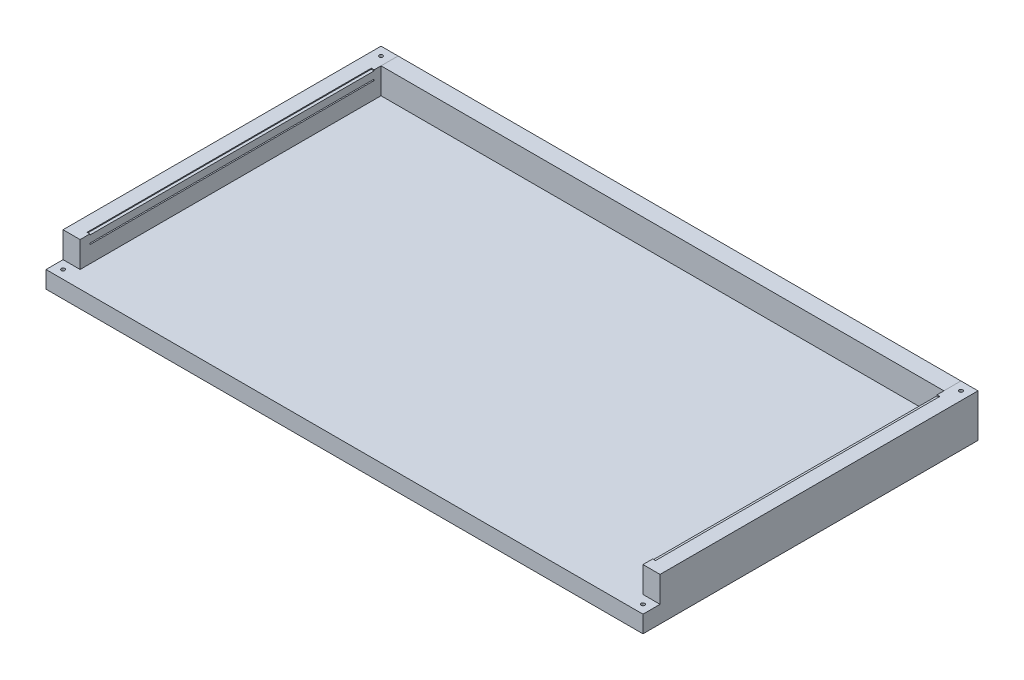
SolidWorks part; units mm, degrees
ref_plane "Front Plane" through (0, 0, 0) normal (0, 0, 1) x (1, 0, 0)
ref_plane "Top Plane" through (0, 0, 0) normal (0, 1, 0) x (1, 0, 0)
ref_plane "Right Plane" through (0, 0, 0) normal (1, 0, 0) x (0, 0, -1)
sketch "Sketch3" plane through (0, 0, 0) normal (0, 0, 1) x (1, 0, 0)
  line L1 (-990, 60) -> (990, 60)
  line L3 (-1050, 0) -> (1050, 0)
  line L5 (-1050, 151.2) -> (-990, 151.2)
  line L6 (-990, 151.2) -> (-990, 60)
  line L7 (0, 0) -> (0, 60) construction
  line L8 (990, 151.2) -> (990, 60)
  line L9 (1050, 151.2) -> (990, 151.2)
  line L11 (1050, 151.2) -> (1050, 0)
  line L12 (-1050, 151.2) -> (-1050, 0)
  dimension "D3" = 60
  dimension "D4" = 91.2
  dimension "D5" = 60
  dimension "D1" = 1980
extrude "Boss-Extrude1" add sketch "Sketch3" along normal mid plane 1118.5
sketch "Sketch4" plane through (0, 0, 0) normal (0, 1, 0) x (1, 0, 0)
  line L0 (-990, 559.25) -> (-990, 499.25)
  line L1 (-990, -559.25) -> (-990, 559.25) construction
  line L2 (-990, 499.25) -> (990, 499.25)
  line L3 (990, -559.25) -> (990, 559.25) construction
  line L4 (990, 499.25) -> (990, 559.25)
  line L5 (990, 559.25) -> (-990, 559.25)
  dimension "D1" = 60
extrude "Boss-Extrude2" add sketch "Sketch4" along normal up to surface (151.2 mm away) from surface at 0 separate body up to face at (-1020, 151.2, 0) starting at face at (0, 0, 0)
sketch "Sketch6" plane through (0, 0, 0) normal (0, 0, 1) x (1, 0, 0)
  line L0 (1000, 151.2) -> (-1000, 151.2)
  line L1 (-990, 151.2) -> (-990, 0) construction
  line L2 (-1000, 151.2) -> (-1000, 147.9)
  line L3 (-1000, 147.9) -> (1000, 147.9)
  line L4 (1000, 147.9) -> (1000, 151.2)
  line L7 (-1000, 122.9) -> (1000, 122.9)
  line L8 (1000, 122.9) -> (1000, 118.5)
  line L9 (1000, 118.5) -> (-1000, 118.5)
  line L10 (-1000, 118.5) -> (-1000, 122.9)
  line L11 (990, 151.2) -> (990, 60) construction
  line L12 (-1050, 0) -> (1050, 0) construction
  dimension "D2" = 10
  dimension "D5" = 4.4
  dimension "D1" = 3.3
  dimension "D6" = 118.5
  dimension "D3" = 10
  dimension "D4" = 25
extrude "Cut-Extrude2" cut sketch "Sketch6" against normal mid plane 1000 from offset 25
sketch "Sketch7" plane through (0, 0, 0) normal (0, 1, 0) x (1, 0, 0)
  line L0 (1050, -559.25) -> (1050, 559.25) construction
  line L1 (0, -559.25) -> (0, 0) construction
  line L2 (990, -559.25) -> (-990, -559.25) construction
  line L3 (1050, 0) -> (-1050, 0) construction
  line L4 (1050, -559.25) -> (1050, 559.25) construction
  line L5 (-1050, -559.25) -> (-1050, 559.25) construction
  line L6 (1050, 559.25) -> (990, 559.25) construction
  circle A0 centre (1020, 529.25) radius 6.35
  circle A2 centre (-1020, 529.25) radius 6.35
  dimension "D1" = 12.7
  dimension "D2" = 30
  dimension "D3" = 30
extrude "Cut-Extrude3" cut sketch "Sketch7" against normal through all from surface at 151.2 starting at face at (1007.5, 151.2, 12.5)
sketch "Sketch8" plane through (0, 0, 0) normal (0, 1, 0) x (1, 0, 0)
  line L0 (-1050, -559.25) -> (-1050, 559.25) construction
  line L1 (1050, -559.25) -> (-1050, -559.25)
  line L2 (1050, -559.25) -> (1050, -619.25)
  line L3 (1050, -619.25) -> (-1050, -619.25)
  line L4 (-1050, -559.25) -> (-1050, -619.25)
  dimension "D1" = 60
extrude "Boss-Extrude3" add sketch "Sketch8" along normal up to surface (60 mm away) from surface at 0 up to face at (0, 60, 0) starting at face at (1020, 0, -535.6)
sketch "Sketch9" plane through (0, 0, 0) normal (0, 1, 0) x (1, 0, 0)
  line L0 (-1050, -619.25) -> (1050, -619.25) construction
  line L1 (-1050, -559.25) -> (-1050, -619.25) construction
  line L2 (0, 559.25) -> (0, -619.25) construction
  line L3 (1050, 559.25) -> (-1050, 559.25) construction
  circle A0 centre (-1020, -589.25) radius 6.35
  circle A1 centre (1020, -589.25) radius 6.35
  point P11 (0, 0)
  dimension "D3" = 12.7
  dimension "D1" = 30
  dimension "D2" = 30
extrude "Cut-Extrude4" cut sketch "Sketch9" along normal up to surface (60 mm away) from surface at 0 up to face at (0, 60, 294.625) starting at face at (1020, 0, -535.6)
equation "\"absorber_plate_width\" = 1000mm"
equation "\"absorber_plate_length\" = 2000mm"
equation "\"absorber_plate_thickness\" = 4mm"
equation "\"D1@Boss-Extrude1\"=\"absorber_plate_width\"-\"pipe_distances\"/2+\"pipe_OD\"+\"frame_thickness\"+\"insulation_thickness\"*2"
equation "\"groove_depth\" = 10mm"
equation "\"frame_thickness\" = 60mm"
equation "\"insulation_thickness\" = 50mm"
equation "\"D5@Sketch3\"=\"frame_thickness\""
equation "\"D3@Sketch3\"=\"frame_thickness\""
equation "\"D1@Sketch4\"=\"frame_thickness\""
equation "\"D2@Sketch6\"=\"groove_depth\""
equation "\"glass_thickness\" = 3mm"
equation "\"D1@Sketch3\"=\"absorber_plate_length\"-\"groove_depth\"*2"
equation "\"D5@Sketch6\"=\"absorber_plate_thickness\"*1.1"
equation "\"D1@Sketch6\"=\"glass_thickness\"*1.1"
equation "\"D3@Sketch6\"=\"groove_depth\""
equation "\"pipe_distances\" = 100mm"
equation "\"pipe_OD\" = 8.5mm"
equation "\"pipe_ID\" = 7.8mm"
equation "\"pipe_straight_length\" = 850mm"
equation "\"D6@Sketch6\"=\"frame_thickness\"+\"insulation_thickness\"+\"pipe_OD\""
equation "\"absorber_to_glass\" = 25mm"
equation "\"D1@Cut-Extrude2\"=\"absorber_plate_width\""
equation "\"D19@Cut-Extrude2\"=\"insulation_thickness\"/2"
equation "\"D4@Sketch3\"=\"insulation_thickness\"+\"absorber_plate_thickness\"*1.1+\"absorber_to_glass\"+\"pipe_OD\"+\"glass_thickness\"*1.1"
equation "\"D1@Sketch8\"=\"frame_thickness\""
equation "\"D4@Sketch6\"=\"absorber_to_glass\""
